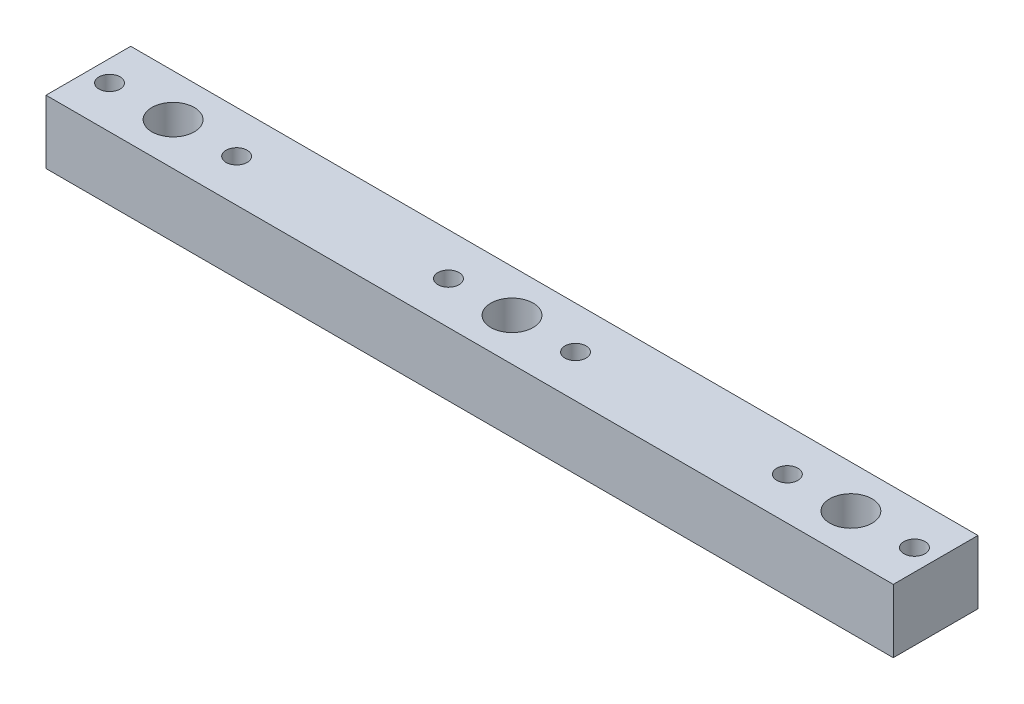
SolidWorks part; units mm, degrees
ref_plane "Front Plane" through (0, 0, 0) normal (0, 0, 1) x (1, 0, 0)
ref_plane "Top Plane" through (0, 0, 0) normal (0, 1, 0) x (1, 0, 0)
ref_plane "Right Plane" through (0, 0, 0) normal (1, 0, 0) x (0, 0, -1)
sketch "Sketch1" plane through (0, 0, 0) normal (0, 1, 0) x (1, 0, 0)
  line L1 (0, 0) -> (200, 0)
  line L2 (0, 0) -> (0, 20)
  line L3 (0, 20) -> (200, 20)
  line L4 (200, 0) -> (200, 20)
  circle A0 centre (20, 10) radius 5
  circle A1 centre (35, 10) radius 2.5
  circle A2 centre (5, 10) radius 2.5
  circle A3 centre (180, 10) radius 5
  circle A4 centre (195, 10) radius 2.5
  circle A5 centre (165, 10) radius 2.5
  circle A6 centre (100, 10) radius 5
  circle A7 centre (115, 10) radius 2.5
  circle A8 centre (85, 10) radius 2.5
  point P23 (0, 0)
  dimension "D1" = 200
  dimension "D2" = 20
extrude "Boss-Extrude1" add sketch "Sketch1" along normal blind 15
